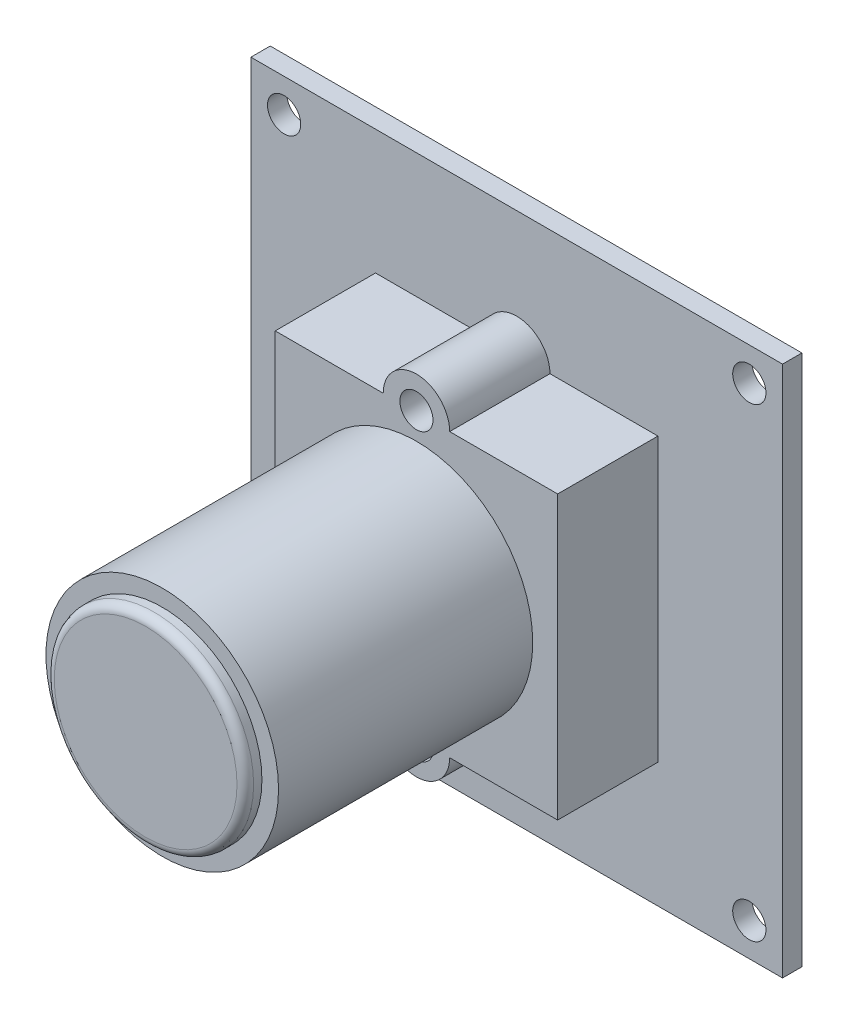
SolidWorks part; units mm, degrees
ref_plane "Front Plane" through (0, 0, 0) normal (0, 0, 1) x (1, 0, 0)
ref_plane "Top Plane" through (0, 0, 0) normal (0, 1, 0) x (1, 0, 0)
ref_plane "Right Plane" through (0, 0, 0) normal (1, 0, 0) x (0, 0, -1)
sketch "Sketch1" plane through (0, 0, 0) normal (0, 0, 1) x (1, 0, 0)
  circle A0 centre (0, 0) radius 7
  dimension "D1" = 14
extrude "Boss-Extrude1" add sketch "Sketch1" along normal blind 15.3
sketch "Sketch2" plane through (0, 0, 15.3) normal (0, 0, 1) x (1, 0, 0)
  circle A0 centre (0, 0) radius 6
  dimension "D1" = 12
extrude "Boss-Extrude2" add sketch "Sketch2" along normal blind 1
fillet "Fillet1" radius 0.5 1 edges at (6, 0, 16.3)
sketch "Sketch3" plane through (0, 0, 0) normal (1, 0, 0) x (0, 0, -1)
  line L0 (-16.3, 0) -> (7.2, 0) construction
  line L1 (-16.3, 5.5) -> (-16.3, -5.5) construction
  line L3 (7.2, -16) -> (6.0361, -16)
  line L4 (7.2, -16) -> (7.2, 16)
  line L5 (7.2, 16) -> (6.0361, 16)
  line L6 (6.0361, -16) -> (6.0361, 16)
  point P9 (6.618, -16)
  dimension "D1" = 23.5
  dimension "D2" = 32
  dimension "D3" = 16
extrude "Boss-Extrude3" add sketch "Sketch3" along normal mid plane 32 separate body
sketch "Sketch4" plane through (0, 0, -6.0361) normal (0, 0, 1) x (1, 0, 0)
  line L1 (-8.5, -8.5) -> (8.5, -8.5)
  line L2 (-8.5, -8.5) -> (-8.5, 8.5)
  line L3 (-8.5, 8.5) -> (8.5, 8.5)
  line L4 (8.5, -8.5) -> (8.5, 8.5)
  line L5 (-8.5, -8.5) -> (8.5, 8.5) construction
  line L6 (-8.5, 8.5) -> (8.5, -8.5) construction
  point P0 (0, 0)
  dimension "D1" = 17
  dimension "D2" = 17
extrude "Boss-Extrude4" add sketch "Sketch4" along normal up to surface (6.0361 mm away) up to face at (7, 0, 0)
sketch "Sketch5" plane through (0, 0, -6.0361) normal (0, 0, 1) x (1, 0, 0)
  line L0 (-16, 16) -> (-16, -16) construction
  line L1 (16, 16) -> (-16, 16) construction
  circle A0 centre (-14, 14) radius 1
  circle A1 centre (14, 14) radius 1
  circle A2 centre (14, -14) radius 1
  circle A3 centre (-14, -14) radius 1
  dimension "D1" = 2
  dimension "D2" = 2
  dimension "D3" = 2
  dimension "D4" = 2
  dimension "D5" = 2
extrude "Cut-Extrude1" cut sketch "Sketch5" against normal blind 4
sketch "Sketch6" plane through (0, 0, 0) normal (0, 0, 1) x (1, 0, 0)
  line L0 (8.5, 8.5) -> (-8.5, 8.5) construction
  line L1 (-8.5, -8.5) -> (8.5, -8.5) construction
  circle A0 centre (0, 8.5) radius 2
  circle A1 centre (0, -8.5) radius 2
  dimension "D1" = 4
extrude "Boss-Extrude5" add sketch "Sketch6" against normal up to surface (6.0361 mm away) up to face at (15, 14, -6.0361)
sketch "Sketch7" plane through (0, 0, 0) normal (0, 0, 1) x (1, 0, 0)
  circle A0 centre (0, 8.5951) radius 0.9953
  circle A1 centre (0, -8.5951) radius 1.0112
extrude "Cut-Extrude2" cut sketch "Sketch7" against normal blind 4
